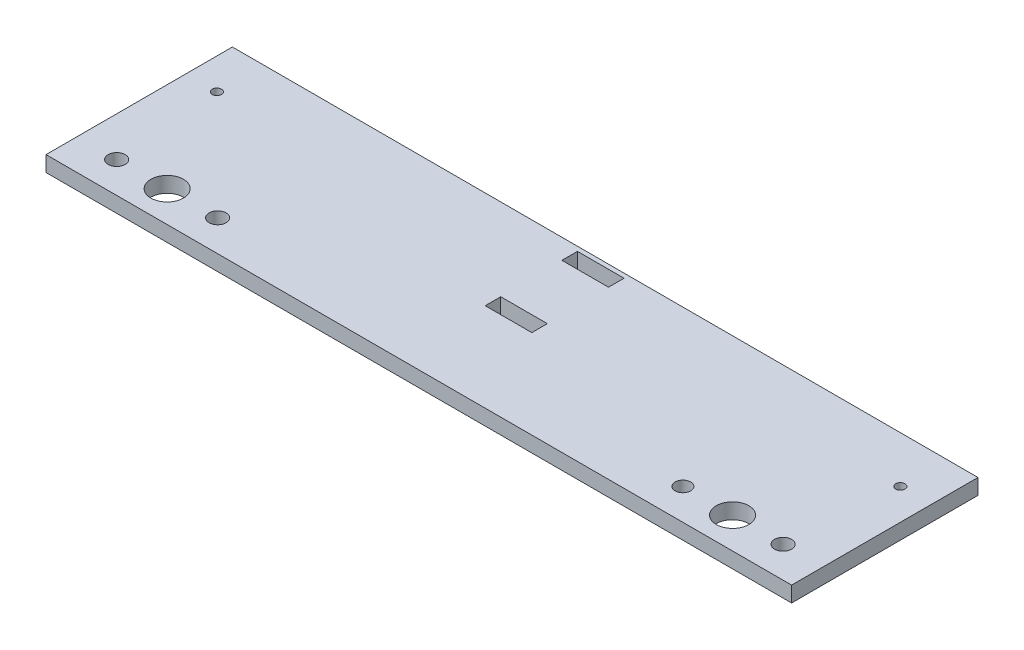
SolidWorks part; units mm, degrees
ref_plane "Front Plane" through (0, 0, 0) normal (0, 0, 1) x (1, 0, 0)
ref_plane "Top Plane" through (0, 0, 0) normal (0, 1, 0) x (1, 0, 0)
ref_plane "Right Plane" through (0, 0, 0) normal (1, 0, 0) x (0, 0, -1)
sketch "Sketch1" plane through (0, 0, 0) normal (0, 1, 0) x (1, 0, 0)
  line L0 (0, 0) -> (0, 64.2675) construction
  line L1 (-120, -45.2146) -> (120, -45.2146)
  line L2 (-120, -45.2146) -> (-120, 14.7854)
  line L3 (-120, 14.7854) -> (120, 14.7854)
  line L4 (120, -45.2146) -> (120, 14.7854)
  line L5 (-7.1893, -16.6479) -> (7.8107, -16.6479)
  line L6 (-7.5, 8.3521) -> (7.5, 8.3521)
  line L7 (-7.5, 8.3521) -> (-7.5, 13.3521)
  line L8 (-7.5, 13.3521) -> (7.5, 13.3521)
  line L9 (7.5, 8.3521) -> (7.5, 13.3521)
  line L10 (-7.1893, -16.6479) -> (-7.1893, -11.6479)
  line L11 (-7.1893, -11.6479) -> (7.8107, -11.6479)
  line L12 (7.8107, -16.6479) -> (7.8107, -11.6479)
  circle A0 centre (-91, -35.2146) radius 5.2482
  circle A1 centre (91, -35.2146) radius 5.2482
  circle A2 centre (-110, -0.2146) radius 1.5
  circle A3 centre (110, -0.2146) radius 1.5
  circle A4 centre (-74.75, -35.2146) radius 2.75
  circle A5 centre (-107.25, -35.2146) radius 2.75
  circle A6 centre (107.25, -35.2146) radius 2.75
  circle A7 centre (75, -35.2146) radius 2.5
  point P0 (0, 0)
  dimension "D11" = 3
  dimension "D1" = 240
  dimension "D2" = 60
  dimension "D3" = 91
  dimension "D4" = 120
  dimension "D5" = 10
  dimension "D6" = 5
  dimension "D7" = 15
  dimension "D8" = 7.5
  dimension "D9" = 20
  dimension "D10" = 5
extrude "Boss-Extrude1" add sketch "Sketch1" along normal blind 5
